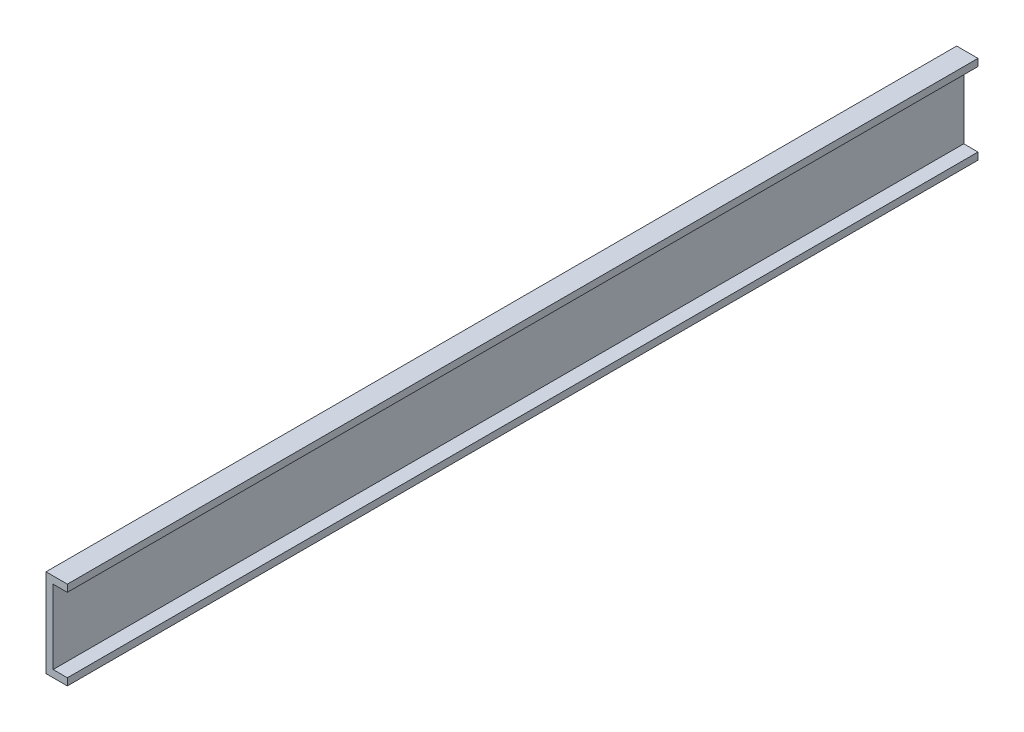
SolidWorks part; units mm, degrees
material "Chrome Stainless Steel"
ref_plane "Front Plane" through (0, 0, 0) normal (0, 0, 1) x (1, 0, 0)
ref_plane "Top Plane" through (0, 0, 0) normal (0, 1, 0) x (1, 0, 0)
ref_plane "Right Plane" through (0, 0, 0) normal (1, 0, 0) x (0, 0, -1)
sketch "Sketch1" plane through (0, 0, 0) normal (1, 0, 0) x (0, 0, -1)
  line L1 (0, 0) -> (406.4, 0)
  line L2 (0, 0) -> (0, 39.37)
  line L3 (0, 39.37) -> (406.4, 39.37)
  line L4 (406.4, 0) -> (406.4, 39.37)
  dimension "D1" = 406.4
  dimension "D2" = 39.37
extrude "Boss-Extrude1" add sketch "Sketch1" along normal blind 9.525
sketch "Sketch2" plane through (0, 0, 0) normal (0, 0, 1) x (1, 0, 0)
  line L0 (9.525, 39.37) -> (9.525, 0) construction
  line L1 (9.525, 36.195) -> (3.175, 36.195)
  line L2 (9.525, 36.195) -> (9.525, 3.175)
  line L3 (9.525, 3.175) -> (3.175, 3.175)
  line L4 (3.175, 36.195) -> (3.175, 3.175)
  line L5 (9.525, 39.37) -> (0, 39.37) construction
  dimension "D1" = 6.35
  dimension "D2" = 33.02
  dimension "D3" = 3.175
extrude "Cut-Extrude1" cut sketch "Sketch2" against normal through all
